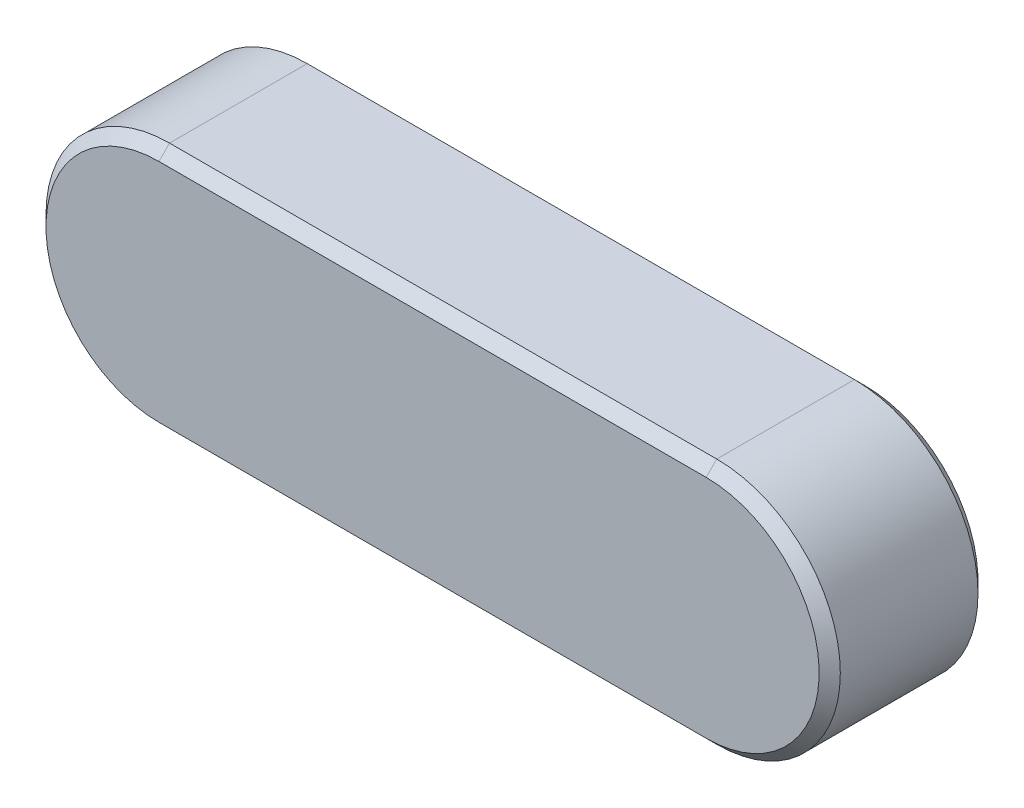
SolidWorks part; units mm, degrees
ref_plane "Front" through (0, 0, 0) normal (0, 0, 1) x (1, 0, 0)
ref_plane "Top" through (0, 0, 0) normal (0, 1, 0) x (1, 0, 0)
ref_plane "Right" through (0, 0, 0) normal (1, 0, 0) x (0, 0, -1)
other "Configuration Table"
sketch "Sketch1" plane through (0, 0, 0) normal (0, 0, 1) x (1, 0, 0)
  line L0 (-31, 7) -> (0, 7)
  line L1 (0, -7) -> (-31, -7)
  arc A0 (0, 7) -> (0, -7) centre (0, 0) cw
  arc A1 (-31, -7) -> (-31, 7) centre (-31, 0) cw
  dimension "L" = 45
  dimension "b" = 14
extrude "BaseKey" add sketch "Sketch1" along normal mid plane 9
sketch "Sketch2" plane through (0, 0, 0) normal (0, 0, 1) x (1, 0, 0)
  line L1 (-38, 7) -> (7, 7)
  line L2 (-38, 7) -> (-38, -7)
  line L3 (-38, -7) -> (7, -7)
  line L4 (7, 7) -> (7, -7)
  line L6 (0, -7) -> (-31, -7) construction
  line L7 (-31, 7) -> (0, 7) construction
  arc A2 (0, -7) -> (0, 7) centre (0, 0) ccw construction
  arc A3 (-31, 7) -> (-31, -7) centre (-31, 0) ccw construction
extrude "Extrude1" [suppressed] add sketch "Sketch2" along normal mid plane 9
sketch "Sketch3" plane through (0, 0, 0) normal (0, 0, 1) x (1, 0, 0)
  line L0 (7, 7) -> (-31, 7)
  line L1 (-31, -7) -> (7, -7)
  line L2 (7, -7) -> (7, 7)
  line L5 (-31, 7) -> (0, 7) construction
  arc A0 (-31, 7) -> (-31, -7) centre (-31, 0) ccw
  arc A1 (0, -7) -> (0, 7) centre (0, 0) ccw construction
  arc A4 (-31, 7) -> (-31, -7) centre (-31, 0) ccw construction
extrude "Extrude2" [suppressed] add sketch "Sketch3" along normal mid plane 9
chamfer "Chamfer1" distance 0.6 angle 45 8 edges at (7, 0, -4.5) (-15.5, -7, -4.5) (-38, 0, -4.5) (-15.5, 7, -4.5) (-38, 0, 4.5) (-15.5, -7, 4.5) (7, 0, 4.5) (-15.5, 7, 4.5)
equation "\"D1@Extrude1\"=\"h@BaseKey\""
equation "\"D1@Extrude2\"=\"h@BaseKey\""
